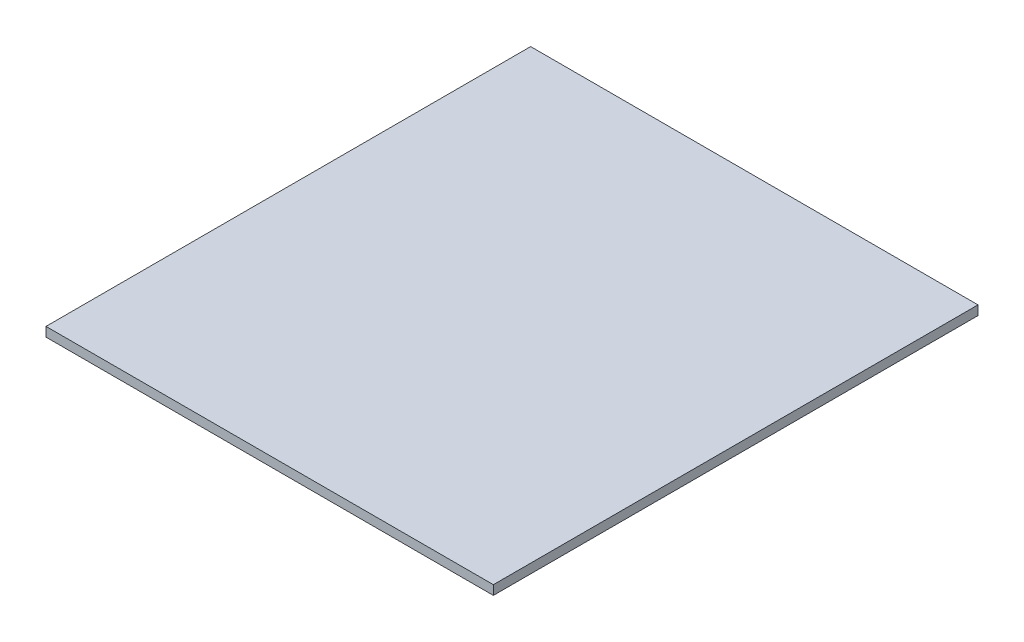
SolidWorks part; units mm, degrees
ref_plane "Front Plane" through (0, 0, 0) normal (0, 0, 1) x (1, 0, 0)
ref_plane "Top Plane" through (0, 0, 0) normal (0, 1, 0) x (1, 0, 0)
ref_plane "Right Plane" through (0, 0, 0) normal (1, 0, 0) x (0, 0, -1)
sketch "Sketch1" plane through (0, 0, 0) normal (0, 1, 0) x (1, 0, 0)
  line L1 (-152.4, 165.1) -> (152.4, 165.1)
  line L2 (-152.4, 165.1) -> (-152.4, -165.1)
  line L3 (-152.4, -165.1) -> (152.4, -165.1)
  line L4 (152.4, 165.1) -> (152.4, -165.1)
  line L5 (-152.4, 165.1) -> (152.4, -165.1) construction
  line L6 (-152.4, -165.1) -> (152.4, 165.1) construction
  point P0 (0, 0)
  dimension "D1" = 304.8
  dimension "D2" = 330.2
extrude "Boss-Extrude1" add sketch "Sketch1" along normal blind 6.35
